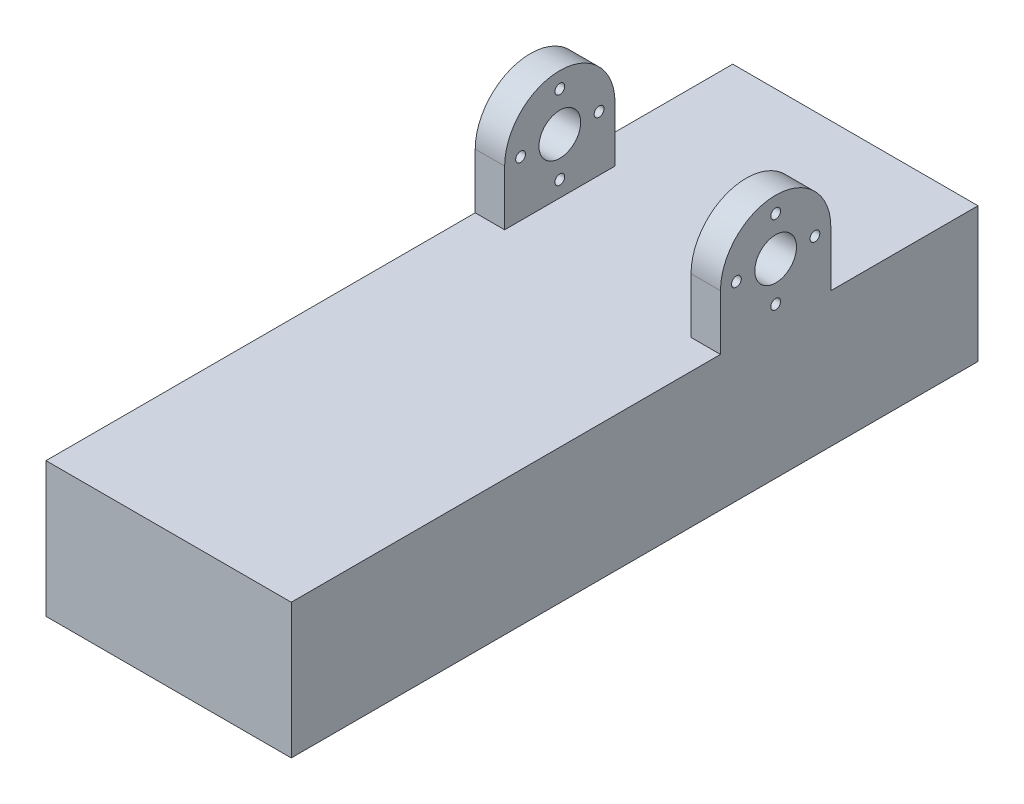
SolidWorks part; units mm, degrees
ref_plane "Front Plane" through (0, 0, 0) normal (0, 0, 1) x (1, 0, 0)
ref_plane "Top Plane" through (0, 0, 0) normal (0, 1, 0) x (1, 0, 0)
ref_plane "Right Plane" through (0, 0, 0) normal (1, 0, 0) x (0, 0, -1)
sketch "Sketch1" plane through (0, 0, 0) normal (0, 0, 1) x (1, 0, 0)
  line L1 (-25, 0) -> (25, 0)
  line L2 (-25, 0) -> (-25, -170)
  line L3 (-25, -170) -> (25, -170)
  line L4 (25, 0) -> (25, -170)
  dimension "D1" = 170
  dimension "D2" = 50
extrude "Boss-Extrude1" add sketch "Sketch1" against normal blind 55
sketch "Sketch2" plane through (0, 0, 0) normal (0, 0, 1) x (1, 0, 0)
  line L0 (25, 0) -> (-25, 0) construction
  line L1 (-17, 0) -> (17, 0)
  line L2 (-17, 0) -> (-17, -27)
  line L3 (-17, -27) -> (17, -27)
  line L4 (17, 0) -> (17, -27)
  line L5 (-25, 0) -> (-25, -170) construction
  dimension "D1" = 8
  dimension "D2" = 34
  dimension "D3" = 27
extrude "Cut-Extrude1" cut sketch "Sketch2" against normal through all
sketch "Sketch3" plane through (25, 0, 0) normal (1, 0, 0) x (0, 0, -1)
  line L0 (0, -170) -> (0, 0) construction
  line L1 (55, -27) -> (0, -27)
  line L2 (55, -27) -> (55, -24)
  line L3 (55, -24) -> (0, -24)
  line L4 (0, -27) -> (0, -24)
  line L5 (55, -170) -> (55, 0) construction
  line L7 (0, 0) -> (10, 0)
  line L8 (0, 0) -> (0, -24)
  line L9 (0, -24) -> (10, -24)
  line L10 (10, 0) -> (10, -24)
  line L11 (55, 0) -> (45, 0)
  line L12 (55, 0) -> (55, -24)
  line L13 (55, -24) -> (45, -24)
  line L14 (45, 0) -> (45, -24)
  circle A0 centre (27.5, -12.75) radius 10.25
  circle A1 centre (27.5, -12.75) radius 4.25
  circle A2 centre (27.5, -12.75) radius 8
  circle A3 centre (27.5, -4.75) radius 1
  circle A4 centre (35.5, -12.75) radius 1
  circle A5 centre (27.5, -20.75) radius 1
  circle A6 centre (19.5, -12.75) radius 1
  point P32 (27.5, -12.75)
  line M7 (0, 0) -> (0, -170)
  line M9 (55, -170) -> (55, 0)
  line M10 (55, 0) -> (0, 0)
  dimension "D2" = 11.25
  dimension "D3" = 27.5
  dimension "D4" = 20.5
  dimension "D7" = 8.5
  dimension "D8" = 16
  dimension "D9" = 4
  dimension "D1" = 3
  dimension "D5" = 10
  dimension "D6" = 10
extrude "Cut-Extrude2" cut sketch "Sketch3" against normal through all contours L14 L3 M10 M9 | L10 L3 M10 M7 | A2 A6 | A2 A6 | A1 | A2 A5 | A2 A5 | A2 A4 | A2 A4 | A2 A3 | A2 A3
sketch "Sketch4" plane through (0, 0, -10) normal (0, 0, 1) x (1, 0, 0)
  line L0 (-25, -24) -> (-17, -24) construction
  line L1 (-17, 0) -> (-19, 0)
  line L2 (-17, 0) -> (-17, -24)
  line L3 (-17, -24) -> (-19, -24)
  line L4 (-19, 0) -> (-19, -24)
  line L5 (0, 0) -> (0, -13.53) construction
  line L6 (19, 0) -> (19, -24)
  line L7 (17, -24) -> (19, -24)
  line L8 (17, 0) -> (17, -24)
  line L9 (17, 0) -> (19, 0)
  dimension "D1" = 2
extrude "Cut-Extrude3" cut sketch "Sketch4" against normal through all
sketch "Sketch5" plane through (25, 0, 0) normal (1, 0, 0) x (0, 0, -1)
  line L1 (10, 0) -> (45, 0)
  line L2 (10, 0) -> (10, -24)
  line L3 (10, -24) -> (45, -24)
  line L4 (45, 0) -> (45, -24)
  line L5 (38.75, -12.75) -> (38.75, -24)
  line L6 (16.25, -12.75) -> (10, -12.75)
  line L7 (16.25, -12.75) -> (16.25, -24)
  line L8 (16.25, -24) -> (10, -24)
  line L9 (10, -12.75) -> (10, -24)
  line L10 (38.75, -12.75) -> (45, -12.75)
  line L11 (38.75, -12.75) -> (38.75, -24)
  line L12 (38.75, -24) -> (45, -24)
  line L13 (45, -12.75) -> (45, -24)
  circle A0 centre (27.5, -12.75) radius 11.25
  line M8 (45, -24) -> (45, 0)
  line M9 (45, 0) -> (10, 0)
  line M10 (10, 0) -> (10, -24)
  dimension "D1" = 22.5
extrude "Cut-Extrude4" cut sketch "Sketch5" against normal through all contours A0 L10 L4 L6 M9 M10 | L7 L6 L2 L3 | L10 L5 L3 M8
sketch "Sketch6" plane through (0, 0, 0) normal (0, 0, 1) x (1, 0, 0)
  line L1 (-19, -24) -> (19, -24)
  line L2 (-19, -24) -> (-19, -34)
  line L3 (-19, -34) -> (19, -34)
  line L4 (19, -24) -> (19, -34)
  dimension "D1" = 10
extrude "Cut-Extrude5" cut sketch "Sketch6" against normal through all
sketch "Sketch8" plane through (25, 0, 0) normal (1, 0, 0) x (0, 0, -1)
  line L0 (55, -170) -> (55, -24) construction
  line L1 (0, -170) -> (0, -24) construction
  line L2 (41.75, -132.5) -> (13.25, -132.5)
  line L3 (27.5, -132.5) -> (27.5, -179)
  line L4 (41.75, -179) -> (13.25, -179)
  line L5 (13.25, -132.5) -> (13.25, -179)
  line L7 (41.75, -132.5) -> (41.75, -179)
  line L11 (27.5, -167.75) -> (55, -167.75)
  line L12 (27.5, -167.75) -> (27.5, -170)
  line L13 (27.5, -170) -> (55, -170)
  line L14 (55, -167.75) -> (55, -170)
  line L16 (27.5, -167.75) -> (0, -167.75)
  line L17 (27.5, -167.75) -> (27.5, -170)
  line L18 (27.5, -170) -> (0, -170)
  line L19 (0, -167.75) -> (0, -170)
  circle A0 centre (27.5, -167.75) radius 10.25
  circle A1 centre (27.5, -12.75) radius 10.25
  line M4 (0, -24) -> (0, -170)
  line M5 (0, -170) -> (55, -170)
  line M6 (55, -170) -> (55, -24)
  dimension "D1" = 27.5
  dimension "D2" = 20.5
  dimension "D3" = 155
  dimension "D4" = 14.25
  dimension "D5" = 11.25
  dimension "D6" = 46.5
  dimension "D7" = 13.25
extrude "Cut-Extrude7" cut sketch "Sketch8" against normal through all contours A0 L3 L2 L5 L16 | A0 L11 L7 L2 L3 | L11 L7 M5 M6 | L5 L16 M4 M5 | A0 L16 L5 M5 | A0 L13 L7 L11 | L3 A0 L16 | L11 A0 L3 | L16 A0 L18 L3 | A0 L11 L3 M5
sketch "Sketch9" plane through (0, 0, 0) normal (0, 0, 1) x (1, 0, 0)
  line L0 (-25, -167.75) -> (25, -167.75) construction
  line L1 (17, -167.75) -> (-17, -167.75)
  line L2 (17, -167.75) -> (17, -132.5)
  line L3 (17, -132.5) -> (-17, -132.5)
  line L4 (-17, -167.75) -> (-17, -132.5)
  line L5 (-25, -132.5) -> (25, -132.5) construction
  line L7 (-25, -24) -> (-25, -167.75) construction
  line L9 (25, -167.75) -> (25, -24) construction
  dimension "D1" = 8
  dimension "D2" = 8
extrude "Cut-Extrude8" cut sketch "Sketch9" against normal through all
sketch "Sketch11" plane through (25, 0, 0) normal (1, 0, 0) x (0, 0, -1)
  line L0 (27.5, -157.5) -> (27.5, -147.5)
  line L2 (27.5, -147.5) -> (55, -147.5)
  line L3 (27.5, -147.5) -> (27.5, -167.75)
  line L4 (27.5, -167.75) -> (55, -167.75)
  line L5 (55, -147.5) -> (55, -167.75)
  line L6 (27.5, -147.5) -> (0, -147.5)
  line L7 (27.5, -147.5) -> (27.5, -167.75)
  line L8 (27.5, -167.75) -> (0, -167.75)
  line L9 (0, -147.5) -> (0, -167.75)
  circle A0 centre (27.5, -167.75) radius 10.25
  arc A1 (38.75, -12.75) -> (16.25, -12.75) centre (27.5, -12.75) ccw construction
  line M1 (0, -167.75) -> (13.25, -167.75)
  line M2 (13.25, -167.75) -> (13.25, -132.5)
  line M4 (41.75, -132.5) -> (41.75, -167.75)
  line M5 (41.75, -167.75) -> (55, -167.75)
  line M6 (55, -167.75) -> (55, -24)
  line M12 (0, -24) -> (0, -167.75)
  dimension "D1" = 155
  dimension "D2" = 20.5
  dimension "D3" = 10
extrude "Cut-Extrude9" cut sketch "Sketch11" against normal through all contours A0 L0 L6 L8 M2 | A0 L4 L2 L0 M4 | L2 M4 M5 M6 | L6 M2 M12 M1
sketch "Sketch12" plane through (25, 0, 0) normal (1, 0, 0) x (0, 0, -1)
  line L1 (13.25, -132.5) -> (41.75, -132.5)
  line L2 (13.25, -132.5) -> (13.25, -147.5)
  line L3 (13.25, -147.5) -> (41.75, -147.5)
  line L4 (41.75, -132.5) -> (41.75, -147.5)
extrude "Boss-Extrude2" add sketch "Sketch12" against normal blind 8
ref_plane "Plane1" through (0, 0, 0) normal (1, 0, 0) x (0, 0, -1)
mirror "Mirror1" about plane through (0, 0, 0) normal (1, 0, 0) of "Boss-Extrude2"
sketch "Sketch14" plane through (0, 0, 0) normal (0, 0, 1) x (1, 0, 0)
  line L0 (17, -148.55) -> (17, -158.75) construction
  line L1 (-17, -132.5) -> (17, -132.5)
  line L2 (-17, -132.5) -> (-17, -147.5)
  line L3 (-17, -147.5) -> (17, -147.5)
  line L4 (17, -132.5) -> (17, -147.5)
  line L5 (-17, -147.5) -> (17, -147.5)
  line L6 (-17, -147.5) -> (-17, -157.75)
  line L7 (-17, -157.75) -> (17, -157.75)
  line L8 (17, -147.5) -> (17, -157.75)
  line M11 (-17, -147.5) -> (-17, -132.5)
  line M12 (-17, -132.5) -> (17, -132.5)
  line M13 (17, -132.5) -> (17, -147.5)
  dimension "D1" = 10.25
extrude "Boss-Extrude3" add sketch "Sketch14" against normal blind 13.25 contours L3 M11 M13 M12 | L8 L3 L6 L7
ref_plane "Plane2" through (0, 0, -27.5) normal (0, 0, 1) x (1, 0, 0)
mirror "Mirror2" about plane through (0, 0, -27.5) normal (0, 0, 1) of "Boss-Extrude3"
sketch "Sketch16" plane through (25, 0, 0) normal (1, 0, 0) x (0, 0, -1)
  line L0 (41.75, -132.5) -> (13.25, -132.5) construction
  line L1 (13.25, -132.5) -> (13.25, -147.5) construction
  circle A1 centre (16.5, -135.75) radius 2.5
  circle A2 centre (16.5, -135.75) radius 4.5
  circle A3 centre (38.5, -135.75) radius 4.5
  dimension "D1" = 3.25
  dimension "D2" = 3.25
  dimension "D3" = 2
extrude "Cut-Extrude13" cut sketch "Sketch16" against normal blind 8 contours A1 | A2 A1 | A3
mirror "Mirror3" about plane through (0, 0, 0) normal (1, 0, 0) of "Cut-Extrude13"
sketch "Sketch17" plane through (25, 0, 0) normal (1, 0, 0) x (0, 0, -1)
  line L0 (55, -147.5) -> (55, -24) construction
  line L1 (27.5, -1.5) -> (55, -1.5)
  line L2 (27.5, -1.5) -> (27.5, -51.5)
  line L3 (27.5, -51.5) -> (55, -51.5)
  line L4 (55, -1.5) -> (55, -51.5)
  line L8 (55, -51.5) -> (0, -51.5)
  line L9 (55, -51.5) -> (55, -157.75)
  line L10 (55, -157.75) -> (0, -157.75)
  line L11 (0, -51.5) -> (0, -157.75)
  arc A0 (38.75, -12.75) -> (16.25, -12.75) centre (27.5, -12.75) ccw construction
  circle M2 centre (16.5, -135.75) radius 4.5
  circle M3 centre (38.5, -135.75) radius 4.5
  line M4 (0, -147.5) -> (55, -147.5)
  line M5 (55, -147.5) -> (55, -24)
  line M11 (0, -24) -> (0, -147.5)
  dimension "D1" = 50
extrude "Cut-Extrude15" cut sketch "Sketch17" against normal through all contours L3 L8 M11 M4 M5 M2 M3 | L11 L10 L9 M4 | M3 | M2
sketch "Sketch18" plane through (25, 0, 0) normal (1, 0, 0) x (0, 0, -1)
  line L1 (38.75, -24) -> (-71.25, -24)
  line L2 (38.75, -24) -> (38.75, -51.5)
  line L3 (38.75, -51.5) -> (-71.25, -51.5)
  line L4 (-71.25, -24) -> (-71.25, -51.5)
  line L6 (38.75, -24) -> (68.75, -24)
  line L7 (38.75, -24) -> (38.75, -51.5)
  line L8 (38.75, -51.5) -> (68.75, -51.5)
  line L9 (68.75, -24) -> (68.75, -51.5)
  line M8 (0, -24) -> (0, -51.5)
  line M9 (0, -51.5) -> (55, -51.5)
  line M10 (55, -51.5) -> (55, -24)
  line M11 (55, -24) -> (38.75, -24)
  line M15 (16.25, -24) -> (0, -24)
  dimension "D1" = 110
  dimension "D2" = 30
extrude "Boss-Extrude4" add sketch "Sketch18" against normal blind 50 contours L1 L4 L3 M8 | L9 L6 L8 M10 | L2 L1 M15 M8 M9 | L2 M11 M9 M10
